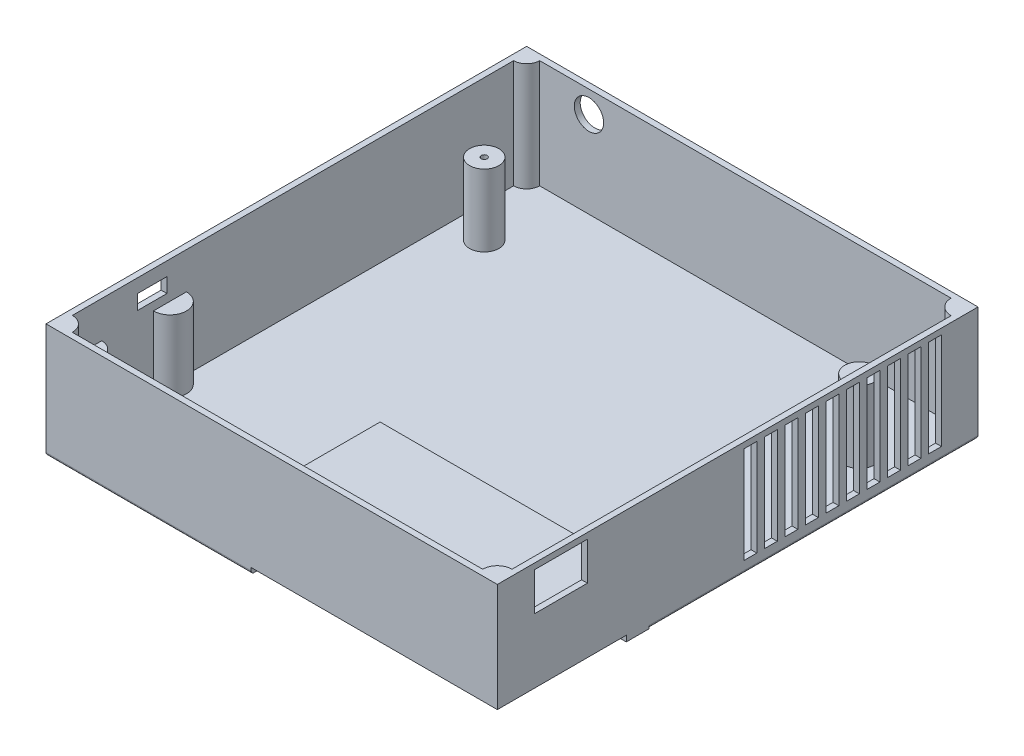
SolidWorks part; units mm, degrees
ref_plane "Front Plane" through (0, 0, 0) normal (0, 0, 1) x (1, 0, 0)
ref_plane "Top Plane" through (0, 0, 0) normal (0, 1, 0) x (1, 0, 0)
ref_plane "Right Plane" through (0, 0, 0) normal (1, 0, 0) x (0, 0, -1)
sketch "Sketch1" plane through (0, 0, 0) normal (0, 1, 0) x (1, 0, 0)
  line L1 (51.3202, -138.8034) -> (-102.6798, -138.8034)
  line L2 (51.3202, -138.8034) -> (51.3202, 25.1966)
  line L3 (51.3202, 25.1966) -> (-102.6798, 25.1966)
  line L4 (-102.6798, -138.8034) -> (-102.6798, 25.1966)
  line L5 (51.3202, -138.8034) -> (-102.6798, 25.1966) construction
  line L6 (51.3202, 25.1966) -> (-102.6798, -138.8034) construction
  point P0 (-25.6798, -56.8034)
  dimension "D1" = 154
  dimension "D2" = 164
extrude "Boss-Extrude1" add sketch "Sketch1" along normal blind 39
fillet "Fillet2" radius 1 4 edges at (-102.6798, 0, 56.8034) (-25.6798, 0, 138.8034) (51.3202, 0, 56.8034) (-25.6798, 0, -25.1966)
sketch "Sketch2" plane through (0, 39, 0) normal (0, 1, 0) x (1, 0, 0)
  line L0 (51.3202, 25.1966) -> (-102.6798, 25.1966) construction
  line L1 (-95.6798, 23.1966) -> (44.3202, 23.1966)
  line L2 (-100.6798, 18.1966) -> (-100.6798, 3.1966)
  line L3 (-95.6798, -136.8034) -> (44.3202, -136.8034)
  line L4 (49.3202, 18.1966) -> (49.3202, 3.1966)
  line L5 (-100.6798, -104.1729) -> (-100.6798, -136.8034)
  line L6 (-100.6798, -6.8034) -> (-100.6798, -92.8838)
  line L7 (-102.6798, 25.1966) -> (-102.6798, -138.8034) construction
  line L8 (-102.6798, -138.8034) -> (51.3202, -138.8034) construction
  line L9 (51.3202, -138.8034) -> (51.3202, 25.1966) construction
  line L10 (49.3202, -6.8034) -> (49.3202, -131.8034)
  line L11 (-100.6798, -6.8034) -> (-100.6798, -92.8838)
  line L12 (-100.6798, -104.1729) -> (-100.6798, -121.8034)
  line L13 (49.3202, -6.8034) -> (49.3202, -131.8034)
  line L14 (-96.2342, 23.1966) -> (44.3202, 23.1966)
  line L15 (-100.6798, 18.7511) -> (-100.6798, 3.1966)
  line L16 (-100.6798, -136.8034) -> (44.3202, -136.8034)
  line L17 (49.3202, 18.1966) -> (49.3202, 3.1966)
  line L18 (-97.6393, 19.9534) -> (45.9005, -133.1557) construction
  line L19 (-100.6798, -136.8034) -> (45.772, 19.4118) construction
  line L20 (-100.6798, 18.1966) -> (-100.6798, 18.7511)
  line L23 (-100.6798, 3.1966) -> (-100.6798, -6.8034)
  line L24 (49.3202, 3.1966) -> (49.3202, -6.8034)
  line L25 (49.3202, 3.1966) -> (49.3202, -6.8034)
  line L26 (49.3202, 3.1966) -> (49.3202, -6.8034)
  arc A2 (-95.6798, -136.8034) -> (-100.6798, -131.8034) centre (-100.6798, -136.8034) ccw
  arc A3 (49.3202, -131.8034) -> (44.3202, -136.8034) centre (49.3202, -136.8034) ccw
  arc A7 (-100.6798, -104.1729) -> (-100.6798, -92.8838) centre (-100.6798, -98.5284) ccw
  arc A8 (-100.6798, -131.8034) -> (-100.6798, -121.8034) centre (-100.6798, -126.8034) ccw
  arc A11 (-100.6798, 18.7511) -> (-96.2342, 23.1966) centre (-100.6798, 23.1966) ccw
  arc A12 (44.1323, 23.1966) -> (49.3202, 18.0087) centre (49.3202, 23.1966) ccw
  circle A13 centre (-89.6798, -2.277) radius 5
  circle A14 centre (38.3202, -2.277) radius 5
  circle A15 centre (-89.6798, -2.277) radius 1
  circle A16 centre (38.3202, -2.277) radius 1
  point P0 (-29.0355, -60.4879)
  point P34 (-25.6798, -56.8034)
  dimension "D5" = 10
  dimension "D6" = 10
  dimension "D7" = 2
  dimension "D9" = 10
  dimension "D8" = 2
  dimension "D1" = 2
  dimension "D2" = 2
  dimension "D3" = 2
  dimension "D4" = 2
  dimension "D10" = 28.275
  dimension "D11" = 10
  dimension "D12" = 11
  dimension "D13" = 11
  dimension "D14" = 128
extrude "Cut-Extrude1" cut sketch "Sketch2" against normal blind 37
sketch "Sketch3" plane through (0, 39, 0) normal (0, 1, 0) x (1, 0, 0)
  line L0 (-100.6798, -92.5284) -> (-100.6798, -104.5284)
  line L2 (-100.6798, 18.7511) -> (-100.6798, -92.8838) construction
  line L3 (-100.6798, -121.8034) -> (-100.6798, -131.8034)
  arc A2 (-100.6798, -104.5284) -> (-100.6798, -92.5284) centre (-100.6798, -98.5284) ccw
  arc A4 (-100.6798, -131.8034) -> (-100.6798, -121.8034) centre (-100.6798, -126.8034) ccw
  arc A6 (-100.6798, -131.8034) -> (-100.6798, -121.8034) centre (-100.6798, -126.8034) ccw construction
  circle A7 centre (-89.6798, -2.277) radius 5
  circle A8 centre (38.3202, -2.277) radius 5
  dimension "D1" = 10
  dimension "D2" = 6
extrude "Cut-Extrude2" cut sketch "Sketch3" against normal blind 12.5 and the other way through all
sketch "Sketch4" plane through (0, 0, 0) normal (0, -1, 0) x (1, 0, 0)
  line L0 (-102.6798, 138.8034) -> (51.3202, 138.8034) construction
  line L1 (-28.6798, 136.8034) -> (47.3202, 136.8034)
  line L2 (-28.6798, 136.8034) -> (-28.6798, 95.8034)
  line L3 (-28.6798, 95.8034) -> (47.3202, 95.8034)
  line L4 (47.3202, 136.8034) -> (47.3202, 95.8034)
  line L5 (-28.6798, 136.8034) -> (47.3202, 95.8034) construction
  line L6 (-28.6798, 95.8034) -> (47.3202, 136.8034) construction
  line L7 (51.3202, 138.8034) -> (51.3202, -25.1966) construction
  point P0 (9.3202, 116.3034)
  dimension "D1" = 76
  dimension "D2" = 41
  dimension "D3" = 2
  dimension "D4" = 4
extrude "Cut-Extrude3" cut sketch "Sketch4" against normal blind 20
sketch "Sketch5" plane through (0, 2, 0) normal (0, 1, 0) x (1, 0, 0)
  line L0 (47.3202, -95.8034) -> (-28.6798, -95.8034) construction
  line L1 (-28.6798, -93.8034) -> (51.3202, -93.8034)
  line L2 (-28.6798, -93.8034) -> (-28.6798, -95.8034)
  line L3 (-28.6798, -95.8034) -> (51.3202, -95.8034)
  line L4 (51.3202, -93.8034) -> (51.3202, -95.8034)
  line L5 (-28.6798, -93.8034) -> (51.3202, -95.8034) construction
  line L6 (-28.6798, -95.8034) -> (51.3202, -93.8034) construction
  line L7 (51.3202, -138.8034) -> (51.3202, 25.1966) construction
  line L8 (-28.6798, -95.8034) -> (-28.6798, -136.8034) construction
  line L9 (-95.6798, -136.8034) -> (-28.6798, -136.8034) construction
  line L10 (-28.6798, -93.8034) -> (-33.6798, -93.8034)
  line L11 (-28.6798, -93.8034) -> (-28.6798, -136.8034)
  line L12 (-28.6798, -136.8034) -> (-33.6798, -136.8034)
  line L13 (-33.6798, -93.8034) -> (-33.6798, -136.8034)
  line L14 (-28.6798, -93.8034) -> (-33.6798, -136.8034) construction
  line L15 (-28.6798, -136.8034) -> (-33.6798, -93.8034) construction
  point P0 (11.3202, -94.8034)
  point P11 (-31.1798, -115.3034)
  line M4 (-28.6798, -95.8034) -> (47.3202, -95.8034)
  line M5 (49.3202, -131.8034) -> (49.3202, 18.0087)
  line M18 (-95.6798, -136.8034) -> (-28.6798, -136.8034)
  line M19 (-28.6798, -136.8034) -> (-28.6798, -95.8034)
  dimension "D1" = 2
  dimension "D2" = 5
extrude "Boss-Extrude2" add sketch "Sketch5" along normal blind 18 contours L1 L2 M4 M5 | L10 L13 L2 M18 M19
sketch "Sketch7" plane through (0, 20, 0) normal (0, 1, 0) x (1, 0, 0)
  line L0 (-33.6798, -93.8034) -> (49.3202, -93.8034) construction
  line L1 (-33.6798, -93.8034) -> (51.3202, -93.8034)
  line L2 (-33.6798, -93.8034) -> (-33.6798, -138.8034)
  line L3 (-33.6798, -138.8034) -> (51.3202, -138.8034)
  line L4 (51.3202, -93.8034) -> (51.3202, -138.8034)
  line L5 (-33.6798, -93.8034) -> (51.3202, -138.8034) construction
  line L6 (-33.6798, -138.8034) -> (51.3202, -93.8034) construction
  line L7 (-33.6798, -93.8034) -> (-33.6798, -136.8034) construction
  line L8 (51.3202, -138.8034) -> (51.3202, 25.1966) construction
  line L9 (-102.6798, -138.8034) -> (51.3202, -138.8034) construction
  point P0 (8.8202, -116.3034)
extrude "Boss-Extrude3" add sketch "Sketch7" along normal blind 2
sketch "Sketch8" plane through (51.3202, 0, 0) normal (1, 0, 0) x (0, 0, -1)
  line L0 (-138.8034, 39) -> (25.1966, 39) construction
  line L1 (-126.066, 37) -> (-108.066, 37)
  line L2 (-126.066, 37) -> (-126.066, 24)
  line L3 (-126.066, 24) -> (-108.066, 24)
  line L4 (-108.066, 37) -> (-108.066, 24)
  line L5 (-126.066, 37) -> (-108.066, 24) construction
  line L6 (-126.066, 24) -> (-108.066, 37) construction
  point P0 (-117.066, 30.5)
  dimension "D1" = 18
  dimension "D2" = 13
  dimension "D3" = 2
extrude "Cut-Extrude4" cut sketch "Sketch8" against normal blind 3
sketch "Sketch10" plane through (0, 0, 0) normal (0, -1, 0) x (1, 0, 0)
  line L0 (51.3202, 138.8034) -> (51.3202, -25.1966) construction
  line L1 (47.3202, 138.8034) -> (51.3202, 138.8034)
  line L2 (47.3202, 138.8034) -> (47.3202, 87.0197)
  line L3 (47.3202, 87.0197) -> (51.3202, 87.0197)
  line L4 (51.3202, 138.8034) -> (51.3202, 87.0197)
  line L5 (47.3202, 138.8034) -> (51.3202, 87.0197) construction
  line L6 (47.3202, 87.0197) -> (51.3202, 138.8034) construction
  line L7 (-102.6798, 138.8034) -> (51.3202, 138.8034) construction
  point P0 (49.3202, 112.9116)
  dimension "D1" = 4
extrude "Boss-Extrude4" add sketch "Sketch10" along direction (0, -1, 0) on the side against the normal up to surface (20 mm away)
sketch "Sketch11" plane through (0, 0, 0) normal (0, -1, 0) x (1, 0, 0)
  line L0 (51.3202, 87.0197) -> (51.3202, -25.1966) construction
  line L1 (-32.6841, 138.8034) -> (51.3202, 138.8034)
  line L2 (-32.6841, 138.8034) -> (-32.6841, 94.8034)
  line L3 (-32.6841, 94.8034) -> (51.3202, 94.8034)
  line L4 (51.3202, 138.8034) -> (51.3202, 94.8034)
  line L5 (-32.6841, 138.8034) -> (51.3202, 94.8034) construction
  line L6 (-32.6841, 94.8034) -> (51.3202, 138.8034) construction
  line L8 (-28.6798, 95.8034) -> (47.3202, 95.8034) construction
  line L10 (-102.6798, 138.8034) -> (47.3202, 138.8034) construction
  point P0 (9.3181, 116.8034)
  dimension "D1" = 1
  dimension "D2" = 84.0043
  dimension "D3" = 44
extrude "Cut-Extrude8" cut sketch "Sketch11" against normal blind 2
sketch "Sketch12" plane through (51.3202, 0, 0) normal (1, 0, 0) x (0, 0, -1)
  line L0 (-87.0197, 1) -> (25.1966, 1) construction
  line L1 (-54.684, 37) -> (-50.2756, 37)
  line L2 (-54.684, 37) -> (-54.684, 4)
  line L3 (-54.684, 4) -> (-50.2756, 4)
  line L4 (-50.2756, 37) -> (-50.2756, 4)
  line L5 (-54.684, 37) -> (-50.2756, 4) construction
  line L6 (-54.684, 4) -> (-50.2756, 37) construction
  line L7 (-47.684, 37) -> (-47.684, 4)
  line L8 (-47.684, 37) -> (-43.2756, 37)
  line L9 (-43.2756, 37) -> (-43.2756, 4)
  line L10 (-47.684, 4) -> (-43.2756, 4)
  line L11 (-40.684, 37) -> (-40.684, 4)
  line L12 (-40.684, 37) -> (-36.2756, 37)
  line L13 (-36.2756, 37) -> (-36.2756, 4)
  line L14 (-40.684, 4) -> (-36.2756, 4)
  line L15 (-33.684, 37) -> (-33.684, 4)
  line L16 (-33.684, 37) -> (-29.2756, 37)
  line L17 (-29.2756, 37) -> (-29.2756, 4)
  line L18 (-33.684, 4) -> (-29.2756, 4)
  line L19 (-26.684, 37) -> (-26.684, 4)
  line L20 (-26.684, 37) -> (-22.2756, 37)
  line L21 (-22.2756, 37) -> (-22.2756, 4)
  line L22 (-26.684, 4) -> (-22.2756, 4)
  line L23 (-19.684, 37) -> (-19.684, 4)
  line L24 (-19.684, 37) -> (-15.2756, 37)
  line L25 (-15.2756, 37) -> (-15.2756, 4)
  line L26 (-19.684, 4) -> (-15.2756, 4)
  line L27 (-12.684, 37) -> (-12.684, 4)
  line L28 (-12.684, 37) -> (-8.2756, 37)
  line L29 (-8.2756, 37) -> (-8.2756, 4)
  line L30 (-12.684, 4) -> (-8.2756, 4)
  line L31 (-5.684, 37) -> (-5.684, 4)
  line L32 (-5.684, 37) -> (-1.2756, 37)
  line L33 (-1.2756, 37) -> (-1.2756, 4)
  line L34 (-5.684, 4) -> (-1.2756, 4)
  line L35 (1.316, 37) -> (1.316, 4)
  line L36 (1.316, 37) -> (5.7244, 37)
  line L37 (5.7244, 37) -> (5.7244, 4)
  line L38 (1.316, 4) -> (5.7244, 4)
  line L39 (8.316, 37) -> (8.316, 4)
  line L40 (8.316, 37) -> (12.7244, 37)
  line L41 (12.7244, 37) -> (12.7244, 4)
  line L42 (8.316, 4) -> (12.7244, 4)
  point P0 (-52.4798, 20.5)
  dimension "D1" = 3
  dimension "D2" = 33
  dimension "D3" = 10
extrude "Cut-Extrude9" cut sketch "Sketch12" against normal blind 3
sketch "Sketch13" plane through (0, 0, -25.1966) normal (0, 0, -1) x (-1, 0, 0)
  line L0 (-51.3202, 1) -> (102.6798, 1) construction
  circle A0 centre (79.4148, 31.5) radius 5
  dimension "D1" = 10
  dimension "D2" = 30.5
extrude "Cut-Extrude10" cut sketch "Sketch13" against normal blind 10
sketch "Sketch14" plane through (-102.6798, 0, 0) normal (-1, 0, 0) x (0, 0, 1)
  line L1 (99.5327, 34.3359) -> (109.5327, 34.3359)
  line L2 (99.5327, 34.3359) -> (99.5327, 29.3359)
  line L3 (99.5327, 29.3359) -> (109.5327, 29.3359)
  line L4 (109.5327, 34.3359) -> (109.5327, 29.3359)
  line L5 (99.5327, 34.3359) -> (109.5327, 29.3359) construction
  line L6 (99.5327, 29.3359) -> (109.5327, 34.3359) construction
  point P0 (104.5327, 31.8359)
  dimension "D1" = 10
  dimension "D2" = 5
extrude "Cut-Extrude11" cut sketch "Sketch14" against normal blind 10
sketch "Sketch15" plane through (0, 2, 0) normal (0, -1, 0) x (1, 0, 0)
  line L0 (51.3202, 138.8034) -> (-32.6841, 138.8034) construction
  line L1 (51.3202, 94.8034) -> (51.3202, 138.8034) construction
  line L2 (-32.6841, 138.8034) -> (-32.6841, 94.8034) construction
  circle A0 centre (-30.6841, 116.8034) radius 1
  circle A1 centre (49.3202, 116.8034) radius 1
  dimension "D1" = 22
  dimension "D3" = 2
  dimension "D6" = 2
  dimension "D2" = 22
  dimension "D4" = 2
  dimension "D5" = 2
extrude "Cut-Extrude12" cut sketch "Sketch15" against normal blind 10
